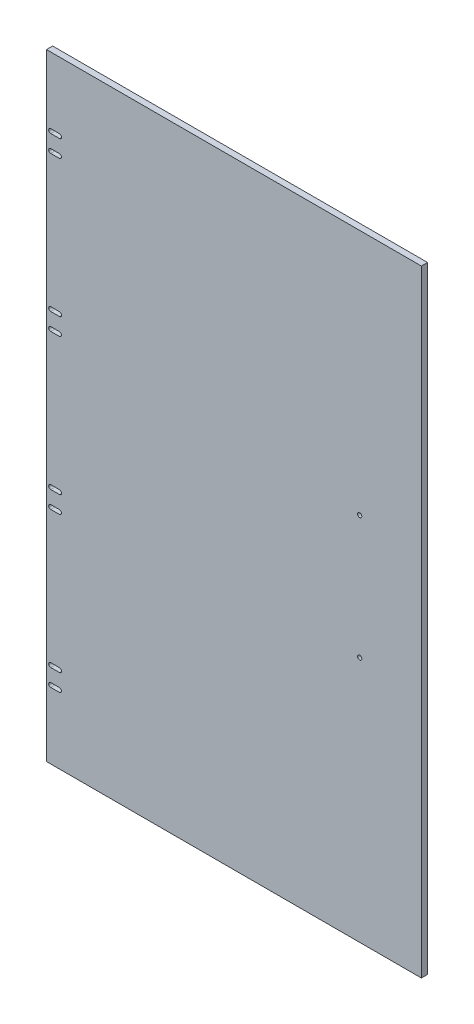
SolidWorks part; units mm, degrees
ref_plane "Plan de face" through (0, 0, 0) normal (0, 0, 1) x (1, 0, 0)
ref_plane "Plan de dessus" through (0, 0, 0) normal (0, 1, 0) x (1, 0, 0)
ref_plane "Plan de droite" through (0, 0, 0) normal (1, 0, 0) x (0, 0, -1)
sketch "Esquisse1" plane through (0, 0, 0) normal (0, 0, 1) x (1, 0, 0)
  line L1 (152, -250) -> (-152, -250)
  line L2 (152, -250) -> (152, 250)
  line L3 (152, 250) -> (-152, 250)
  line L4 (-152, -250) -> (-152, 250)
  line L5 (152, -250) -> (-152, 250) construction
  line L6 (152, 250) -> (-152, -250) construction
  point P0 (0, 0)
  dimension "D1" = 304
  dimension "D2" = 500
extrude "Boss.-Extru.1" add sketch "Esquisse1" along normal blind 5
sketch "Esquisse11" plane through (0, 0, 5) normal (0, 0, 1) x (1, 0, 0)
  line L0 (-152, -250) -> (152, -250) construction
  line L1 (152, -250) -> (152, 250) construction
  point P0 (102, -50)
  point P2 (102, 50)
  dimension "D1" = 100
  dimension "D2" = 50
  dimension "200" = 200
hole_wizard "Dégagement M34" positions "Esquisse11" profile "Esquisse12" hole size "M3" standard "ISO" end condition through all
sketch "Esquisse12" plane through (102, -50, 5) normal (1, 0, 0) x (0, -1, 0)
  line L0 (0, 0) -> (0, 5)
  line L1 (0, 5) -> (1.7, 5)
  line L2 (1.7, 5) -> (1.7, 0)
  line L5 (1.7, 0) -> (0, 0)
  line L11 (0, -6.35) -> (0, 107.95) construction
  dimension "Diamètre du perçage jusqu'au prochain" = 3.4
  dimension "Profondeur du perçage jusqu'au prochain" = 5
sketch "Esquisse15" plane through (0, 0, 5) normal (0, 0, 1) x (1, 0, 0)
  line L0 (-148.5, -194.5) -> (-141.5, -194.5) construction
  line L1 (-148.5, -192.8) -> (-141.5, -192.8)
  line L2 (-148.5, -196.2) -> (-141.5, -196.2)
  line L3 (-141.5, -180.5) -> (-148.5, -180.5) construction
  line L4 (-141.5, -182.2) -> (-148.5, -182.2)
  line L5 (-141.5, -178.8) -> (-148.5, -178.8)
  line L6 (-152, -250) -> (152, -250) construction
  line L7 (-152, 250) -> (-152, -250) construction
  line L8 (-145, -194.5) -> (-145, -180.5) construction
  line L9 (-148.5, -69.5) -> (-141.5, -69.5) construction
  line L10 (-148.5, -67.8) -> (-141.5, -67.8)
  line L11 (-148.5, -71.2) -> (-141.5, -71.2)
  line L12 (-141.5, -55.5) -> (-148.5, -55.5) construction
  line L13 (-141.5, -57.2) -> (-148.5, -57.2)
  line L14 (-141.5, -53.8) -> (-148.5, -53.8)
  line L15 (-148.5, 55.5) -> (-141.5, 55.5) construction
  line L16 (-148.5, 57.2) -> (-141.5, 57.2)
  line L17 (-148.5, 53.8) -> (-141.5, 53.8)
  line L18 (-141.5, 69.5) -> (-148.5, 69.5) construction
  line L19 (-141.5, 67.8) -> (-148.5, 67.8)
  line L20 (-141.5, 71.2) -> (-148.5, 71.2)
  line L21 (-148.5, 180.5) -> (-141.5, 180.5) construction
  line L22 (-148.5, 182.2) -> (-141.5, 182.2)
  line L23 (-148.5, 178.8) -> (-141.5, 178.8)
  line L24 (-141.5, 194.5) -> (-148.5, 194.5) construction
  line L25 (-141.5, 192.8) -> (-148.5, 192.8)
  line L26 (-141.5, 196.2) -> (-148.5, 196.2)
  arc A0 (-148.5, -192.8) -> (-148.5, -196.2) centre (-148.5, -194.5) ccw
  arc A1 (-141.5, -196.2) -> (-141.5, -192.8) centre (-141.5, -194.5) ccw
  arc A2 (-141.5, -182.2) -> (-141.5, -178.8) centre (-141.5, -180.5) ccw
  arc A3 (-148.5, -178.8) -> (-148.5, -182.2) centre (-148.5, -180.5) ccw
  arc A4 (-148.5, -67.8) -> (-148.5, -71.2) centre (-148.5, -69.5) ccw
  arc A5 (-141.5, -71.2) -> (-141.5, -67.8) centre (-141.5, -69.5) ccw
  arc A6 (-141.5, -57.2) -> (-141.5, -53.8) centre (-141.5, -55.5) ccw
  arc A7 (-148.5, -53.8) -> (-148.5, -57.2) centre (-148.5, -55.5) ccw
  arc A8 (-148.5, 57.2) -> (-148.5, 53.8) centre (-148.5, 55.5) ccw
  arc A9 (-141.5, 53.8) -> (-141.5, 57.2) centre (-141.5, 55.5) ccw
  arc A10 (-141.5, 67.8) -> (-141.5, 71.2) centre (-141.5, 69.5) ccw
  arc A11 (-148.5, 71.2) -> (-148.5, 67.8) centre (-148.5, 69.5) ccw
  arc A12 (-148.5, 182.2) -> (-148.5, 178.8) centre (-148.5, 180.5) ccw
  arc A13 (-141.5, 178.8) -> (-141.5, 182.2) centre (-141.5, 180.5) ccw
  arc A14 (-141.5, 192.8) -> (-141.5, 196.2) centre (-141.5, 194.5) ccw
  arc A15 (-148.5, 196.2) -> (-148.5, 192.8) centre (-148.5, 194.5) ccw
  point P2 (-145, -194.5)
  point P7 (-145, -180.5)
  point P24 (-145, -69.5)
  point P29 (-145, -55.5)
  point P38 (-145, 55.5)
  point P43 (-145, 69.5)
  point P52 (-145, 180.5)
  point P57 (-145, 194.5)
  dimension "D1" = 7
  dimension "D2" = 3.4
  dimension "D3" = 14
  dimension "D4" = 55.5
  dimension "D5" = 7
  dimension "D7" = 125
  dimension "D6" = 4
extrude "Enlèv. mat.-Extru.3" cut sketch "Esquisse15" against normal up to next
